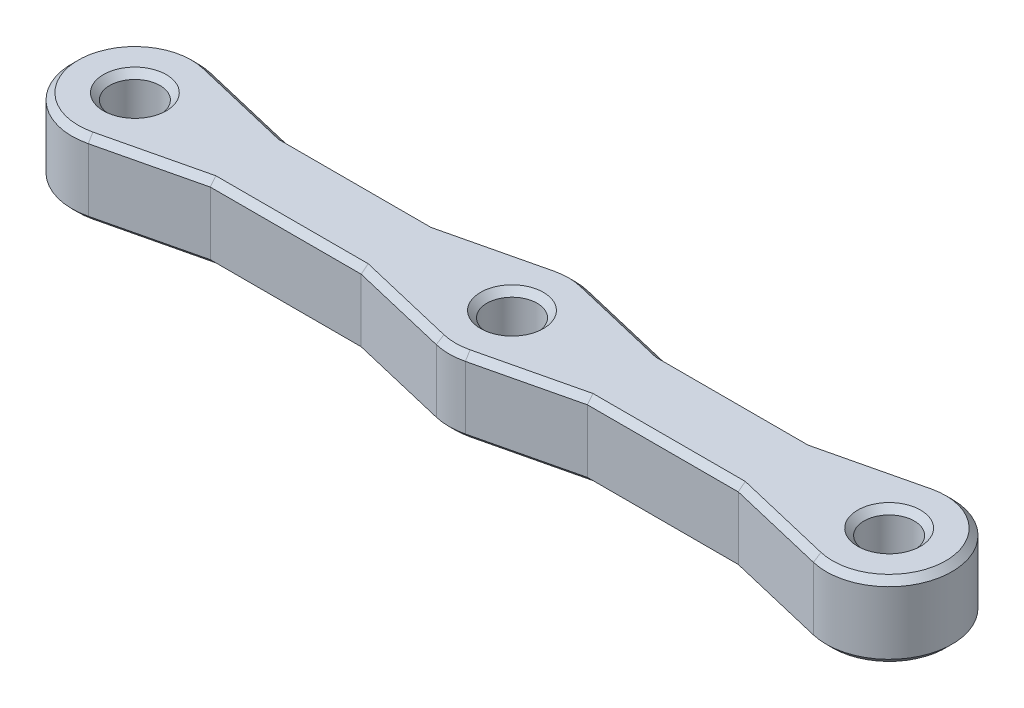
SolidWorks part; units mm, degrees
ref_plane "前视基准面" through (0, 0, 0) normal (0, 0, 1) x (1, 0, 0)
ref_plane "上视基准面" through (0, 0, 0) normal (0, 1, 0) x (1, 0, 0)
ref_plane "右视基准面" through (0, 0, 0) normal (1, 0, 0) x (0, 0, -1)
other "Configuration Table"
sketch "草图1" plane through (0, 0, 0) normal (0, 1, 0) x (1, 0, 0)
  line L0 (-15, 0) -> (15, 0) construction
  line L1 (-13, 1.5) -> (-2, 1.5)
  line L2 (2, -1.5) -> (13, -1.5)
  line L3 (2, 1.5) -> (13, 1.5)
  line L4 (-13, -1.5) -> (-2, -1.5)
  arc A0 (2, 1.5) -> (-2, 1.5) centre (0, 0) ccw
  arc A1 (13, -1.5) -> (13, 1.5) centre (15, 0) ccw
  arc A2 (-13, 1.5) -> (-13, -1.5) centre (-15, 0) ccw
  circle A3 centre (-15, 0) radius 1
  circle A4 centre (0, 0) radius 1
  circle A5 centre (15, 0) radius 1
  arc A6 (-2, -1.5) -> (2, -1.5) centre (0, 0) ccw
  point P6 (0, 0)
  dimension "D1" = 5
  dimension "D3" = 5
  dimension "D4" = 5
  dimension "D5" = 2
  dimension "D6" = 2
  dimension "D7" = 2
  dimension "D2" = 30
  dimension "D8" = 3
extrude "凸台-拉伸1" add sketch "草图1" along normal blind 3
sketch "草图2" plane through (0, 0, 0) normal (0, 1, 0) x (1, 0, 0)
  line L0 (4.5, 1.5) -> (0.5781, 2.4322)
  line L1 (4.5, -1.5) -> (0.5781, -2.4322)
  line L2 (10.5, 1.5) -> (14.4219, 2.4322)
  line L3 (10.5, -1.5) -> (14.4219, -2.4322)
  line L4 (-13, -1.5) -> (-2, -1.5)
  line L5 (2, -1.5) -> (13, -1.5)
  line L6 (13, 1.5) -> (2, 1.5)
  line L7 (-2, 1.5) -> (-13, 1.5)
  line L9 (2, -1.5) -> (4.5, -1.5)
  line L10 (13, 1.5) -> (10.5, 1.5)
  line L12 (0, -1000) -> (0, 49000) construction
  line L13 (10.5, -1.5) -> (13, -1.5)
  line L14 (4.5, 1.5) -> (2, 1.5)
  line L15 (-4.5, 1.5) -> (-2, 1.5)
  line L16 (-10.5, -1.5) -> (-13, -1.5)
  line L17 (-13, 1.5) -> (-10.5, 1.5)
  line L18 (-2, -1.5) -> (-4.5, -1.5)
  line L19 (-10.5, -1.5) -> (-14.4219, -2.4322)
  line L20 (-10.5, 1.5) -> (-14.4219, 2.4322)
  line L21 (-4.5, -1.5) -> (-0.5781, -2.4322)
  line L22 (-4.5, 1.5) -> (-0.5781, 2.4322)
  arc A0 (14.4219, 2.4322) -> (13, 1.5) centre (15, 0) ccw
  arc A1 (-2, 1.5) -> (-0.5781, 2.4322) centre (0, 0) cw
  arc A2 (-13, -1.5) -> (-14.4219, -2.4322) centre (-15, 0) cw
  arc A3 (-0.5781, -2.4322) -> (-2, -1.5) centre (0, 0) cw
  arc A4 (-13, 1.5) -> (-13, -1.5) centre (-15, 0) ccw
  arc A5 (-2, -1.5) -> (2, -1.5) centre (0, 0) ccw
  arc A6 (13, -1.5) -> (13, 1.5) centre (15, 0) ccw
  arc A7 (2, 1.5) -> (-2, 1.5) centre (0, 0) ccw
  arc A9 (0.5781, -2.4322) -> (2, -1.5) centre (0, 0) ccw
  arc A10 (13, -1.5) -> (14.4219, -2.4322) centre (15, 0) ccw
  arc A11 (2, 1.5) -> (0.5781, 2.4322) centre (0, 0) ccw
  arc A12 (-14.4219, 2.4322) -> (-13, 1.5) centre (-15, 0) cw
  dimension "D2" = 2.5
  dimension "D3" = 2.5
  dimension "D4" = 2.5
  dimension "D5" = 2.5
  dimension "D1" = 0
extrude "凸台-拉伸2" add sketch "草图2" along normal up to surface (3 mm away) up to face at (0, 3, 1)
chamfer "倒角1" distance 0.25 angle 45 38 edges at (15, 3, 1) (15, 0, 1) (0, 3, 1) (0, 0, 1) (-15, 3, 1) (-15, 0, 1) (-12.4609, 3, -1.9661) (-12.4609, 0, -1.9661) (-17.5, 3, 0) (-17.5, 0, 0) (-12.4609, 3, 1.9661) (-12.4609, 0, 1.9661) (-7.5, 3, 1.5) (-7.5, 0, 1.5) (-2.5391, 3, 1.9661) (-2.5391, 0, 1.9661) (0, 3, 2.5) (0, 0, 2.5) (2.5391, 3, 1.9661) (2.5391, 0, 1.9661) (7.5, 3, 1.5) (7.5, 0, 1.5) (12.4609, 3, 1.9661) (12.4609, 0, 1.9661) (17.5, 3, 0) (17.5, 0, 0) (12.4609, 3, -1.9661) (12.4609, 0, -1.9661) (7.5, 0, -1.5) (7.5, 3, -1.5) (2.5391, 3, -1.9661) (2.5391, 0, -1.9661) (0, 3, -2.5) (0, 0, -2.5) (-2.5391, 3, -1.9661) (-2.5391, 0, -1.9661) (-7.5, 0, -1.5) (-7.5, 3, -1.5)
